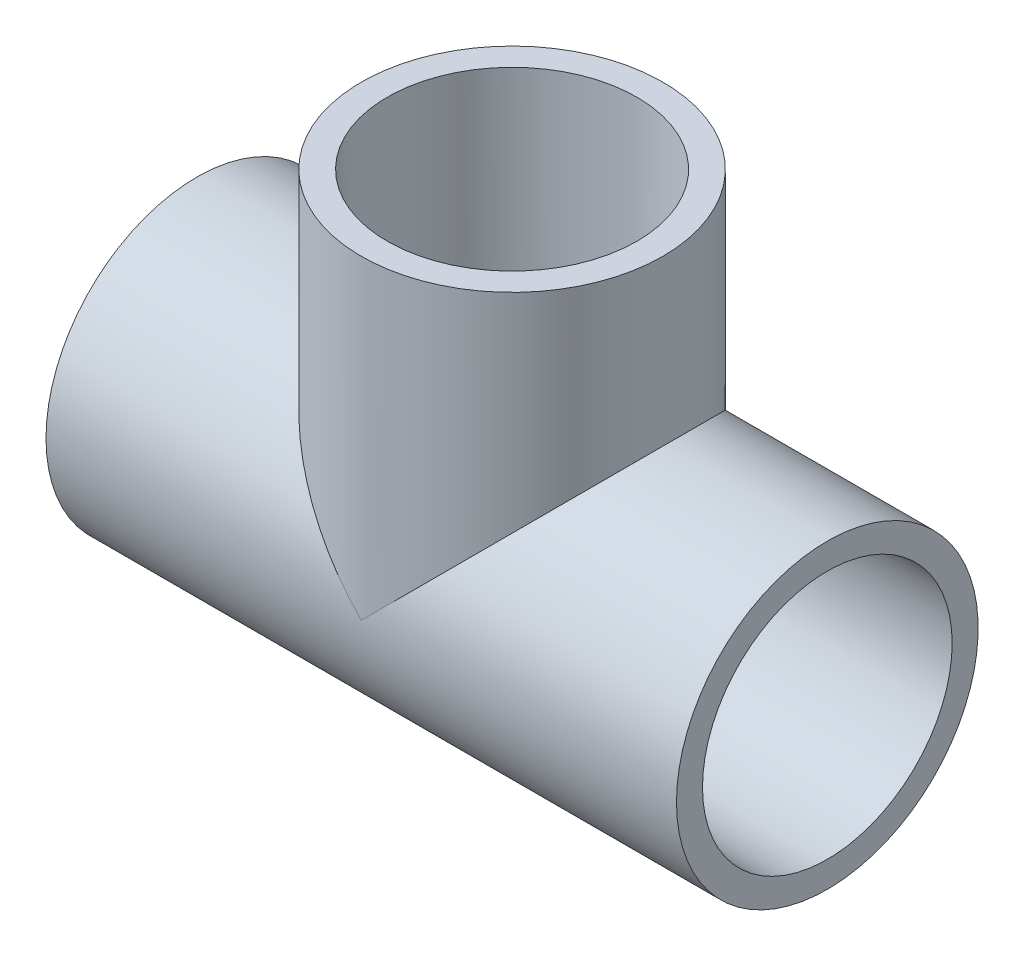
SolidWorks part; units mm, degrees
ref_plane "Front Plane" through (0, 0, 0) normal (0, 0, 1) x (1, 0, 0)
ref_plane "Top Plane" through (0, 0, 0) normal (0, 1, 0) x (1, 0, 0)
ref_plane "Right Plane" through (0, 0, 0) normal (1, 0, 0) x (0, 0, -1)
sketch "Sketch0" plane through (0, 0, 0) normal (0, 0, 1) x (1, 0, 0)
  line L0 (-42.4942, 0) -> (0, 0) construction
  line L1 (0, 0) -> (0, 42.4942) construction
  line L2 (-17.4752, 0) -> (0, 0) construction
  line L3 (0, 0) -> (0, 17.4752) construction
  line L4 (-42.4942, 20.3327) -> (-42.4942, -20.3327) construction
  line L5 (-17.4752, 16.637) -> (-42.4942, 16.8275) construction
  line L6 (-17.4752, 16.637) -> (-17.4752, -16.637) construction
  line L7 (-17.4752, -16.637) -> (-42.4942, -16.8275) construction
  line L8 (-42.4942, 16.8275) -> (-42.4942, -16.8275) construction
  line L9 (-20.3327, 42.4942) -> (20.3327, 42.4942) construction
  line L10 (-16.8275, 42.4942) -> (16.8275, 42.4942) construction
  line L11 (16.8275, 42.4942) -> (16.637, 17.4752) construction
  line L12 (16.637, 17.4752) -> (-16.637, 17.4752) construction
  line L13 (-16.637, 17.4752) -> (-16.8275, 42.4942) construction
  line L14 (-17.4752, 13.3223) -> (-17.4752, -13.3223) construction
  line L15 (-42.4942, 0) -> (-17.4752, 0) construction
  line L16 (0, 42.4942) -> (0, 17.4752) construction
  line L17 (0, 0) -> (17.4752, 0) construction
  line L18 (-13.3223, 17.4752) -> (13.3223, 17.4752) construction
  line L19 (17.4752, 0) -> (42.4942, 0) construction
  dimension "H" = 42.4942
  dimension "G" = 17.4752
  dimension "M" = 40.6654
  dimension "OD A" = 33.655
  dimension "OD B" = 33.274
  dimension "ID" = 26.6446
  dimension "H3" = 42.4942
sketch "Sketch1" plane through (0, 0, 0) normal (0, 0, 1) x (1, 0, 0)
  line L0 (-42.4942, 0) -> (0, 0) construction
  line L1 (-42.4942, 0) -> (0, 0) construction
  line L2 (0, 0) -> (0, -20.3327) construction
  line L3 (-42.4942, -20.3327) -> (-17.4752, -20.3327)
  line L4 (-42.4942, -20.3327) -> (-42.4942, -16.8275)
  line L5 (-42.4942, -16.8275) -> (-17.4752, -16.637)
  line L6 (-17.4752, -20.3327) -> (-17.4752, -16.637)
  line L7 (-17.4752, -20.3327) -> (0, -20.3327) construction
  line L8 (42.4942, -16.8275) -> (17.4752, -16.637)
  line L9 (42.4942, -20.3327) -> (42.4942, -16.8275)
  line L10 (17.4752, -20.3327) -> (17.4752, -16.637)
  line L11 (42.4942, -20.3327) -> (17.4752, -20.3327)
revolve "Revolve1" add sketch "Sketch1" angle 360 about L1
sketch "Sketch2" plane through (0, 0, 0) normal (0, 0, 1) x (1, 0, 0)
  line L0 (16.8275, 42.4942) -> (16.637, 17.4752)
  line L1 (16.637, 17.4752) -> (20.3327, 17.4752)
  line L2 (20.3327, 17.4752) -> (20.3327, 42.4942)
  line L3 (20.3327, 42.4942) -> (16.8275, 42.4942)
  line L4 (0, 0) -> (0, 42.4942) construction
  line L5 (0, 0) -> (0, 42.4942) construction
revolve "Revolve2" add sketch "Sketch2" angle 360 about L5
sketch "Sketch3" plane through (-17.4752, 0, 0) normal (1, 0, 0) x (0, 0, -1)
  circle A0 centre (0, 0) radius 13.3223
  circle A1 centre (0, 0) radius 20.3327
sketch "Sketch4" plane through (-17.4752, 0, 0) normal (1, 0, 0) x (0, 0, -1)
  circle A0 centre (0, 0) radius 20.3327 construction
  circle A1 centre (0, 0) radius 20.3327
extrude "Boss-Extrude1" add sketch "Sketch4" along normal up to vertex (34.9504 mm away) up to point (17.4752, 0, 0)
sketch "Sketch5" plane through (0, 17.4752, 0) normal (0, -1, 0) x (1, 0, 0)
  circle A0 centre (0, 0) radius 20.3327 construction
  circle A1 centre (0, 0) radius 20.3327
extrude "Boss-Extrude2" add sketch "Sketch5" along normal up to vertex (17.4752 mm away) up to point (0, 0, 0)
sketch "Sketch6" plane through (0, 0, 0) normal (0, 0, 1) x (1, 0, 0)
  line L0 (-42.4942, -16.8275) -> (-17.4752, -16.637)
  line L1 (-17.4752, -16.637) -> (-17.4752, -13.3223)
  line L2 (-17.4752, -13.3223) -> (17.4752, -13.3223)
  line L3 (17.4752, -16.637) -> (17.4752, 12.9905) construction
  line L4 (0, -13.3223) -> (0, 0) construction
  line L5 (17.4752, -16.637) -> (17.4752, -13.3223)
  line L6 (42.4942, -16.8275) -> (42.4942, 16.8275) construction
  line L7 (42.4942, -20.3327) -> (42.4942, 20.3327) construction
  line L8 (42.4942, -16.8275) -> (42.4942, 0)
  line L9 (42.4942, 0) -> (-42.4942, 0)
  line L10 (-42.4942, 0) -> (-42.4942, -16.8275)
  line L11 (42.4942, -16.8275) -> (17.4752, -16.637)
revolve "Cut-Revolve1" cut sketch "Sketch6" angle 360 about L9
sketch "Sketch7" plane through (0, 0, 0) normal (0, 0, 1) x (1, 0, 0)
  line L0 (16.8275, 42.4942) -> (16.637, 17.4752)
  line L1 (16.637, 17.4752) -> (13.3223, 17.4752)
  line L2 (13.3223, 17.4752) -> (13.3223, 0)
  line L3 (0, 0) -> (17.4752, 0) construction
  line L4 (13.3223, 0) -> (0, 0)
  line L5 (0, 0) -> (0, 42.4942)
  line L6 (-20.3327, 42.4942) -> (20.3327, 42.4942) construction
  line L7 (0, 42.4942) -> (16.8275, 42.4942)
revolve "Cut-Revolve2" cut sketch "Sketch7" angle 360 about L5
